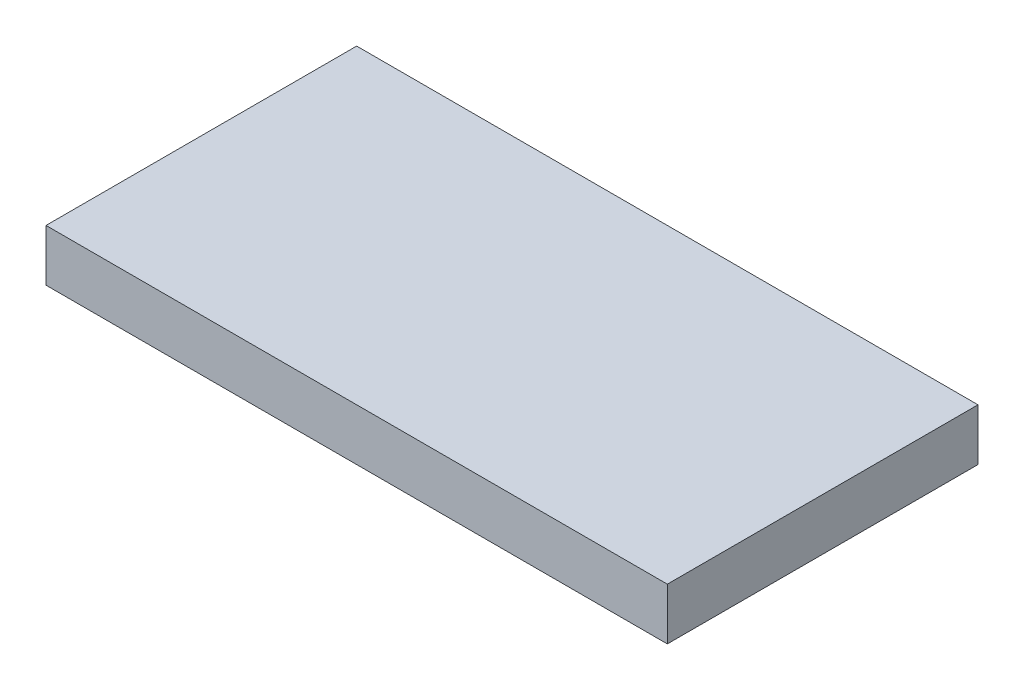
SolidWorks part; units mm, degrees
ref_plane "Front Plane" through (0, 0, 0) normal (0, 0, 1) x (1, 0, 0)
ref_plane "Top Plane" through (0, 0, 0) normal (0, 1, 0) x (1, 0, 0)
ref_plane "Right Plane" through (0, 0, 0) normal (1, 0, 0) x (0, 0, -1)
sketch "Sketch1" plane through (0, 0, 0) normal (0, 1, 0) x (1, 0, 0)
  line L1 (-30, -15) -> (30, -15)
  line L2 (-30, -15) -> (-30, 15)
  line L3 (-30, 15) -> (30, 15)
  line L4 (30, -15) -> (30, 15)
  line L5 (-30, -15) -> (30, 15) construction
  line L6 (-30, 15) -> (30, -15) construction
  point P0 (0, 0)
  dimension "D1" = 60
  dimension "D2" = 30
extrude "Boss-Extrude1" add sketch "Sketch1" along normal mid plane 5
sketch "Sketch2" plane through (0, -2.5, 0) normal (0, -1, 0) x (1, 0, 0)
  line L0 (-30, 0) -> (30, 0) construction
  line L1 (-30, -15) -> (-30, 15) construction
  line L2 (30, 15) -> (30, -15) construction
  line L3 (0, 15) -> (0, -15) construction
  line L4 (-30, 15) -> (30, 15) construction
  line L5 (30, -15) -> (-30, -15) construction
  point P12 (0, 0)
